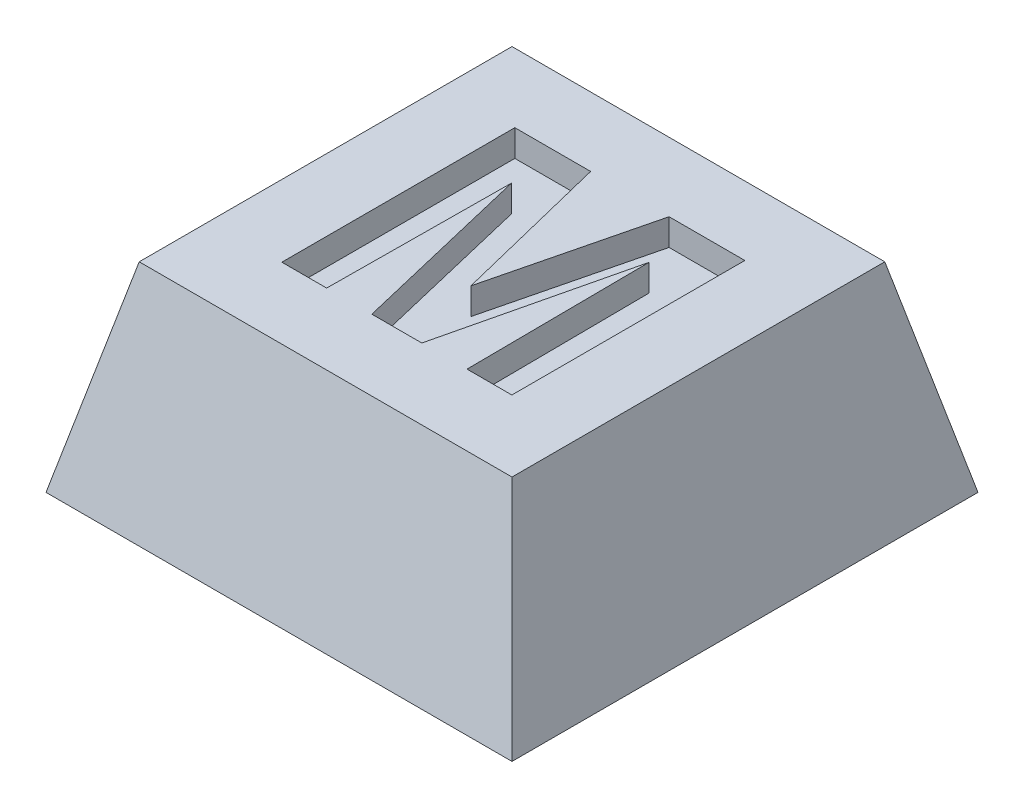
SolidWorks part; units mm, degrees
ref_plane "Front Plane" through (0, 0, 0) normal (0, 0, 1) x (1, 0, 0)
ref_plane "Top Plane" through (0, 0, 0) normal (0, 1, 0) x (1, 0, 0)
ref_plane "Right Plane" through (0, 0, 0) normal (1, 0, 0) x (0, 0, -1)
sketch "Sketch1" plane through (0, 0, 0) normal (0, 1, 0) x (1, 0, 0)
  line L1 (0, 0) -> (7, 0)
  line L2 (0, 0) -> (0, 7)
  line L3 (0, 7) -> (7, 7)
  line L4 (7, 0) -> (7, 7)
  dimension "D1" = 7
  dimension "D2" = 7
extrude "Boss-Extrude1" add sketch "Sketch1" along normal blind 3
sketch "Sketch2" plane through (0, 0, 0) normal (0, 0, 1) x (1, 0, 0)
  line L0 (0, 0) -> (0.7, 3)
  line L1 (0, 3) -> (7, 3) construction
  line L2 (0.7, 3) -> (0, 3)
  line L3 (0, 3) -> (0, 0)
  line L4 (7, 0) -> (6.3, 3)
  line L5 (6.3, 3) -> (7, 3)
  line L6 (7, 3) -> (7, 0)
  dimension "D1" = 0.7
  dimension "D2" = 0.7
extrude "Cut-Extrude1" cut sketch "Sketch2" against normal blind 7
sketch "Sketch3" plane through (0, 0, 0) normal (1, 0, 0) x (0, 0, -1)
  line L0 (0, 0) -> (0.7, 3)
  line L1 (7, 3) -> (0, 3) construction
  line L2 (0.7, 3) -> (0, 3)
  line L3 (0, 3) -> (0, 0)
  line L4 (7, 3) -> (6.3, 3)
  line L5 (6.3, 3) -> (7, 0)
  line L6 (7, 3) -> (7, 0)
  dimension "D1" = 0.7
  dimension "D2" = 0.7
extrude "Cut-Extrude2" cut sketch "Sketch3" along normal blind 11
sketch "Sketch4" plane through (0, 0, 0) normal (0, -1, 0) x (1, 0, 0)
  line L0 (3.5, 0) -> (3.5, -7) construction
  line L1 (0, 0) -> (7, 0) construction
  line L2 (7, -7) -> (0, -7) construction
  line L3 (0, -3.5) -> (7, -3.5) construction
  line L4 (0, -7) -> (0, 0) construction
  line L5 (7, 0) -> (7, -7) construction
  circle A0 centre (3.5, -3.5) radius 1.8
  dimension "D1" = 3.6
extrude "Cut-Extrude3" cut sketch "Sketch4" against normal blind 0.8
sketch "Sketch5" plane through (0, 3, 0) normal (0, 1, 0) x (1, 0, 0)
  text T0 "M" font "Arial" height 3.5
extrude "Cut-Extrude4" cut sketch "Sketch5" against normal blind 0.4
